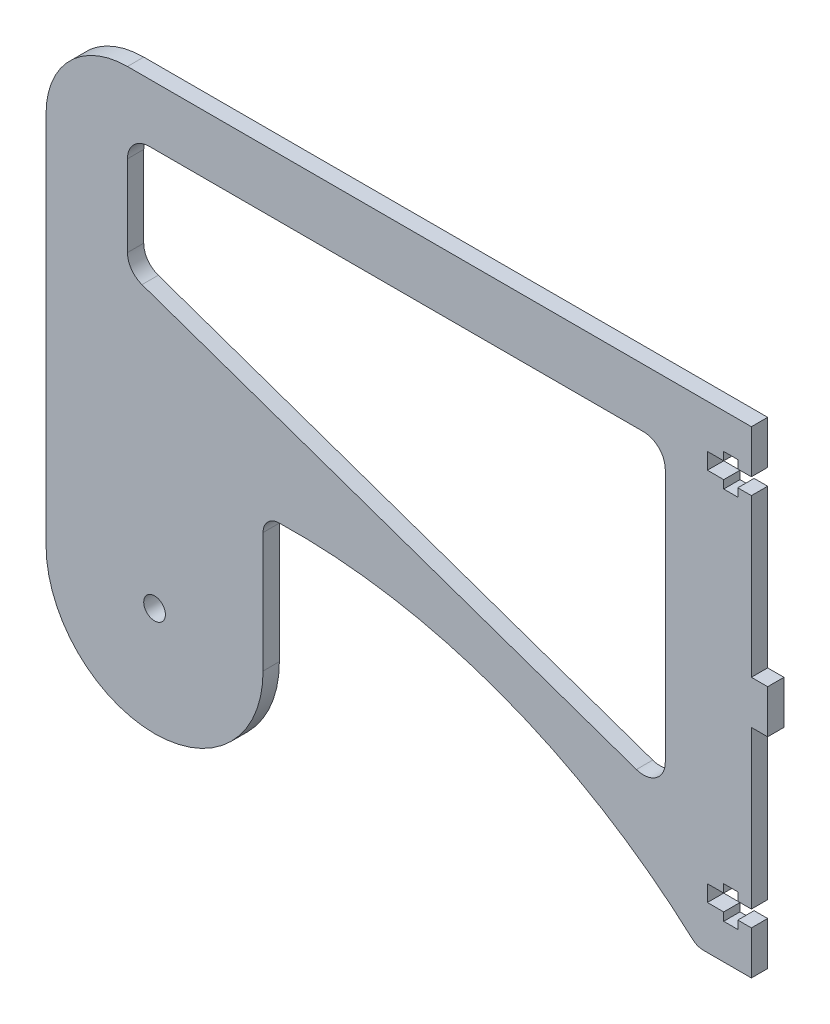
SolidWorks part; units mm, degrees
ref_plane "前视基准面" through (0, 0, 0) normal (0, 0, 1) x (1, 0, 0)
ref_plane "上视基准面" through (0, 0, 0) normal (0, 1, 0) x (1, 0, 0)
ref_plane "右视基准面" through (0, 0, 0) normal (1, 0, 0) x (0, 0, -1)
sketch "草图1" plane through (0, 0, 0) normal (0, 0, 1) x (1, 0, 0)
  line L261 (364.0026, 97.7079) -> (354.0026, 97.7079)
  line L278 (364.0026, 97.7079) -> (364.0026, 89.7079)
  line L279 (361.5026, 89.7079) -> (361.5026, 91.2079)
  line L280 (361.5026, 86.7079) -> (361.5026, 85.2079)
  line L281 (364.0026, 86.7079) -> (361.5026, 86.7079)
  line L282 (361.5026, 91.2079) -> (358.9026, 91.2079)
  line L283 (358.9026, 91.2079) -> (358.9026, 89.7079)
  line L284 (358.9026, 89.7079) -> (355.9026, 89.7079)
  line L285 (355.9026, 86.7079) -> (355.9026, 89.7079)
  line L286 (358.9026, 86.7079) -> (355.9026, 86.7079)
  line L287 (358.9026, 85.2079) -> (358.9026, 86.7079)
  line L288 (361.5026, 85.2079) -> (358.9026, 85.2079)
  line L289 (361.5026, 89.7079) -> (364.0026, 89.7079)
  line L291 (364.0026, 9.7079) -> (364.0026, 17.7079)
  line L292 (364.0026, 20.7079) -> (364.0026, 86.7079) construction
  line L293 (361.5026, 20.7079) -> (361.5026, 22.2079)
  line L294 (361.5026, 17.7079) -> (361.5026, 16.2079)
  line L295 (364.0026, 17.7079) -> (361.5026, 17.7079)
  line L296 (361.5026, 22.2079) -> (358.9026, 22.2079)
  line L297 (358.9026, 22.2079) -> (358.9026, 20.7079)
  line L298 (358.9026, 20.7079) -> (355.9026, 20.7079)
  line L299 (355.9026, 17.7079) -> (355.9026, 20.7079)
  line L300 (358.9026, 17.7079) -> (355.9026, 17.7079)
  line L301 (358.9026, 16.2079) -> (358.9026, 17.7079)
  line L302 (361.5026, 16.2079) -> (358.9026, 16.2079)
  line L303 (361.5026, 20.7079) -> (364.0026, 20.7079)
  line L313 (364.0026, 9.7079) -> (355.1684, 9.7079)
  line L316 (364.0026, 53.7079) -> (254.0026, 53.7079) construction
  line L317 (254.0026, 53.7079) -> (254.0026, 13.7079) construction
  line L318 (274.0026, 13.7079) -> (274.0026, 35.8191)
  line L320 (354.0026, 97.7079) -> (249.0026, 97.7079)
  line L321 (234.0026, 82.7079) -> (234.0026, 13.7079)
  line L322 (364.0026, 57.7079) -> (364.0026, 86.7079)
  line L323 (364.0026, 57.7079) -> (367.0026, 57.7079)
  line L324 (367.0026, 57.7079) -> (367.0026, 49.7079)
  line L325 (367.0026, 49.7079) -> (364.0026, 49.7079)
  line L326 (364.0026, 49.7079) -> (364.0026, 20.7079)
  line L327 (253.0026, 86.967) -> (344.1293, 86.967)
  line L328 (348.1293, 82.967) -> (348.1293, 36.1724)
  line L329 (342.8102, 32.3961) -> (251.6836, 64.2263)
  line L330 (249.0026, 68.0025) -> (249.0026, 82.967)
  circle A38 centre (254.0026, 13.7079) radius 2
  circle A43 centre (254.0026, 13.7079) radius 20 construction
  arc A46 (274.0026, 13.7079) -> (234.0026, 13.7079) centre (254.0026, 13.7079) cw
  arc A47 (353.1542, 10.4846) -> (276.9296, 38.8182) centre (279.5943, -70.7116) ccw
  arc A48 (276.9296, 38.8182) -> (274.0026, 35.8191) centre (277.0026, 35.8191) ccw
  arc A49 (355.1684, 9.7079) -> (353.1542, 10.4846) centre (355.1684, 12.7079) cw
  arc A50 (234.0026, 82.7079) -> (249.0026, 97.7079) centre (249.0026, 82.7079) cw
  arc A51 (251.6836, 64.2263) -> (249.0026, 68.0025) centre (253.0026, 68.0025) cw
  arc A52 (249.0026, 82.967) -> (253.0026, 86.967) centre (253.0026, 82.967) cw
  arc A53 (344.1293, 86.967) -> (348.1293, 82.967) centre (344.1293, 82.967) cw
  arc A54 (342.8102, 32.3961) -> (348.1293, 36.1724) centre (344.1293, 36.1724) ccw
  dimension "D1" = 3
  dimension "D3" = 15
  dimension "D4" = 4
  dimension "D2" = 3
extrude "凸台-拉伸1" add sketch "草图1" along normal blind 3
sketch "草图2" plane through (364.0026, 0, 0) normal (1, 0, 0) x (0, 0, -1)
  line L0 (-1.5, 89.7079) -> (-1.5, 86.7079) construction
  line L1 (-3, 89.7079) -> (0, 89.7079) construction
  line L2 (-3, 86.7079) -> (0, 86.7079) construction
  circle A0 centre (-1.5, 88.2079) radius 1.5
